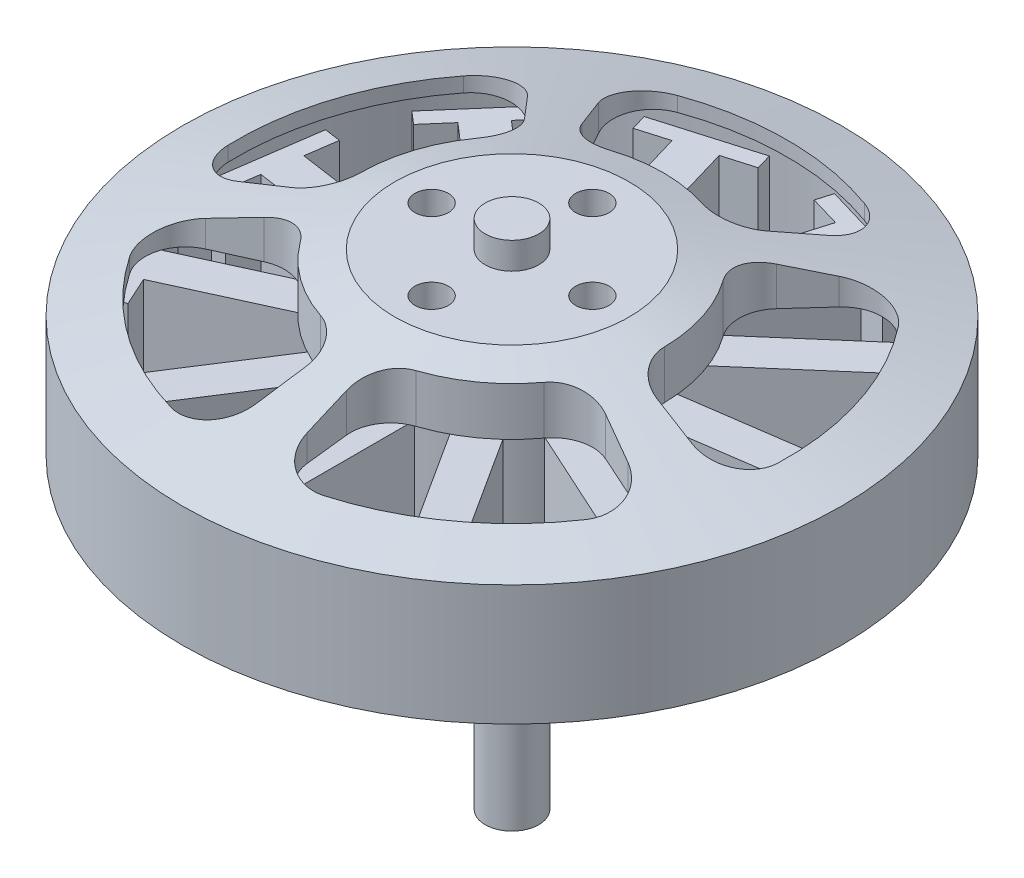
SolidWorks part; units mm, degrees
material "Acero aleado"
ref_plane "Alzado" through (0, 0, 0) normal (0, 0, 1) x (1, 0, 0)
ref_plane "Planta" through (0, 0, 0) normal (0, 1, 0) x (1, 0, 0)
ref_plane "Vista lateral" through (0, 0, 0) normal (1, 0, 0) x (0, 0, -1)
sketch "Croquis1" plane through (0, 0, 0) normal (0, 1, 0) x (1, 0, 0)
  circle A0 centre (0, 0) radius 24.6
  dimension "D1" = 49.2
extrude "Saliente-Extruir1" add sketch "Croquis1" along normal blind 9
sketch "Croquis2" plane through (0, 0, 0) normal (0, 0, 1) x (1, 0, 0)
  line L0 (-24.6, 9) -> (-8.75, 13.3)
  line L1 (-8.75, 13.3) -> (0, 13.3)
  line L2 (0, 13.3) -> (0, 9)
  line L3 (24.6, 9) -> (-24.6, 9) construction
  line L4 (0, 9) -> (-24.6, 9)
  dimension "D1" = 8.75
  dimension "D2" = 4.3
revolve "Revolución1" add sketch "Croquis2" angle 360 about L2
sketch "Croquis4" plane through (0, 0, 0) normal (0, -1, 0) x (1, 0, 0)
  circle A0 centre (0, 0) radius 22.8389
extrude "Cortar-Extruir1" cut sketch "Croquis4" against normal blind 9
sketch "Croquis5" plane through (0, 13.3, 0) normal (0, 1, 0) x (1, 0, 0)
  line L0 (-8.5704, 15.019) -> (-6.9301, 12.1446)
  line L1 (6.9301, 12.1446) -> (8.5704, 15.019)
  line L2 (0, 0) -> (0, 27.6667) construction
  line L3 (11.6356, 12.7921) -> (9.4086, 10.3438)
  line L4 (13.6917, -2.8381) -> (16.9324, -3.5098)
  line L5 (15.7616, -7.1131) -> (12.745, -5.7517)
  line L6 (1.5318, -13.8986) -> (1.8944, -17.1882)
  line L7 (-1.8944, -17.1882) -> (-1.5318, -13.8986)
  line L8 (-12.745, -5.7517) -> (-15.7616, -7.1131)
  line L9 (-16.9324, -3.5098) -> (-13.6917, -2.8381)
  line L10 (-9.4086, 10.3438) -> (-11.6356, 12.7921)
  arc A0 (3.4173, 10.7719) -> (-3.4173, 10.7719) centre (0, 0) ccw
  arc A1 (6.9844, 19.3273) -> (-6.9844, 19.3273) centre (0, 0) ccw
  arc A2 (6.9301, 12.1446) -> (3.4173, 10.7719) centre (4.3245, 13.6314) cw
  arc A3 (-6.9301, 12.1446) -> (-3.4173, 10.7719) centre (-4.3245, 13.6314) ccw
  arc A4 (8.5704, 15.019) -> (6.9844, 19.3273) centre (5.9648, 16.5059) ccw
  arc A5 (-8.5704, 15.019) -> (-6.9844, 19.3273) centre (-5.9648, 16.5059) cw
  arc A6 (11.3007, 0.0786) -> (9.1887, 6.5788) centre (0, 0) ccw
  arc A7 (20.5397, -0.6701) -> (16.2231, 12.615) centre (0, 0) ccw
  arc A8 (13.6917, -2.8381) -> (11.3007, 0.0786) centre (14.3006, 0.0995) cw
  arc A9 (9.4086, 10.3438) -> (9.1887, 6.5788) centre (11.6279, 8.3252) ccw
  arc A10 (16.9324, -3.5098) -> (20.5397, -0.6701) centre (17.5413, -0.5723) ccw
  arc A11 (11.6356, 12.7921) -> (16.2231, 12.615) centre (13.8548, 10.7735) cw
  arc A12 (3.5669, -10.7233) -> (9.0962, -6.706) centre (0, 0) ccw
  arc A13 (5.7098, -19.7415) -> (17.0108, -11.5308) centre (0, 0) ccw
  arc A14 (1.5318, -13.8986) -> (3.5669, -10.7233) centre (4.5137, -13.57) cw
  arc A15 (12.745, -5.7517) -> (9.0962, -6.706) centre (11.511, -8.4862) ccw
  arc A16 (1.8944, -17.1882) -> (5.7098, -19.7415) centre (4.8763, -16.8596) ccw
  arc A17 (15.7616, -7.1131) -> (17.0108, -11.5308) centre (14.5276, -9.8475) cw
  arc A18 (-9.0962, -6.706) -> (-3.5669, -10.7233) centre (0, 0) ccw
  arc A19 (-17.0108, -11.5308) -> (-5.7098, -19.7415) centre (0, 0) ccw
  arc A20 (-12.745, -5.7517) -> (-9.0962, -6.706) centre (-11.511, -8.4862) cw
  arc A21 (-1.5318, -13.8986) -> (-3.5669, -10.7233) centre (-4.5137, -13.57) ccw
  arc A22 (-15.7616, -7.1131) -> (-17.0108, -11.5308) centre (-14.5276, -9.8475) ccw
  arc A23 (-1.8944, -17.1882) -> (-5.7098, -19.7415) centre (-4.8763, -16.8596) cw
  arc A24 (-9.1887, 6.5788) -> (-11.3007, 0.0786) centre (0, 0) ccw
  arc A25 (-16.2231, 12.615) -> (-20.5397, -0.6701) centre (0, 0) ccw
  arc A26 (-9.4086, 10.3438) -> (-9.1887, 6.5788) centre (-11.6279, 8.3252) cw
  arc A27 (-13.6917, -2.8381) -> (-11.3007, 0.0786) centre (-14.3006, 0.0995) ccw
  arc A28 (-11.6356, 12.7921) -> (-16.2231, 12.615) centre (-13.8548, 10.7735) ccw
  arc A29 (-16.9324, -3.5098) -> (-20.5397, -0.6701) centre (-17.5413, -0.5723) cw
  point P65 (0, 0)
  dimension "D1" = 3
  dimension "D2" = 5
extrude "Cortar-Extruir2" cut sketch "Croquis5" against normal through all
sketch "Croquis3" plane through (0, 13.3, 0) normal (0, 1, 0) x (1, 0, 0)
  circle A0 centre (0, 0) radius 2
  dimension "D1" = 4
extrude "Saliente-Extruir2" add sketch "Croquis3" along normal blind 8 from offset 6 offset against normal yes
sketch "Croquis6" plane through (0, 7.3, 0) normal (0, -1, 0) x (1, 0, 0)
  line L0 (-1.4178, 20.2309) -> (-1.4178, 8.6919)
  line L1 (1.4178, 20.2309) -> (1.4178, 8.6919)
  line L2 (0, 0) -> (0, 19.3794) construction
  line L3 (-1.4178, 20.2309) -> (-3.7639, 20.2309)
  line L4 (-3.7639, 20.2309) -> (-3.7639, 21.4518)
  line L5 (-3.7639, 21.4518) -> (3.7639, 21.4518)
  line L6 (3.7639, 21.4518) -> (3.7639, 20.2309)
  line L7 (3.7639, 20.2309) -> (1.4178, 20.2309)
  line L8 (9.745, 17.7858) -> (3.5065, 8.0786)
  line L9 (12.1304, 16.2528) -> (5.8919, 6.5456)
  line L10 (9.745, 17.7858) -> (7.7713, 19.0542)
  line L11 (7.7713, 19.0542) -> (8.4313, 20.0813)
  line L12 (8.4313, 20.0813) -> (14.7641, 16.0115)
  line L13 (14.7641, 16.0115) -> (14.1041, 14.9844)
  line L14 (14.1041, 14.9844) -> (12.1304, 16.2528)
  line L15 (17.8137, 9.6939) -> (7.3175, 4.9004)
  line L16 (18.9916, 7.1146) -> (8.4954, 2.3211)
  line L17 (17.8137, 9.6939) -> (16.8391, 11.828)
  line L18 (16.8391, 11.828) -> (17.9496, 12.3352)
  line L19 (17.9496, 12.3352) -> (21.0768, 5.4876)
  line L20 (21.0768, 5.4876) -> (19.9663, 4.9805)
  line L21 (19.9663, 4.9805) -> (18.9916, 7.1146)
  line L22 (20.2268, -1.4758) -> (8.8052, 0.1663)
  line L23 (19.8232, -4.2825) -> (8.4017, -2.6403)
  line L24 (20.2268, -1.4758) -> (20.5606, 0.8464)
  line L25 (20.5606, 0.8464) -> (21.7691, 0.6727)
  line L26 (21.7691, 0.6727) -> (20.6978, -6.7785)
  line L27 (20.6978, -6.7785) -> (19.4893, -6.6047)
  line L28 (19.4893, -6.6047) -> (19.8232, -4.2825)
  line L29 (16.2179, -12.177) -> (7.4974, -4.6205)
  line L30 (14.3611, -14.3199) -> (5.6405, -6.7635)
  line L31 (16.2179, -12.177) -> (17.7543, -10.4039)
  line L32 (17.7543, -10.4039) -> (18.677, -11.2034)
  line L33 (18.677, -11.2034) -> (13.7473, -16.8925)
  line L34 (13.7473, -16.8925) -> (12.8247, -16.093)
  line L35 (12.8247, -16.093) -> (14.3611, -14.3199)
  line L36 (7.06, -19.012) -> (3.8091, -7.9404)
  line L37 (4.3394, -19.8108) -> (1.0885, -8.7393)
  line L38 (7.06, -19.012) -> (9.3111, -18.351)
  line L39 (9.3111, -18.351) -> (9.6551, -19.5224)
  line L40 (9.6551, -19.5224) -> (2.4322, -21.6432)
  line L41 (2.4322, -21.6432) -> (2.0883, -20.4718)
  line L42 (2.0883, -20.4718) -> (4.3394, -19.8108)
  line L43 (-4.3394, -19.8108) -> (-1.0885, -8.7393)
  line L44 (-7.06, -19.012) -> (-3.8091, -7.9404)
  line L45 (-4.3394, -19.8108) -> (-2.0883, -20.4718)
  line L46 (-2.0883, -20.4718) -> (-2.4322, -21.6432)
  line L47 (-2.4322, -21.6432) -> (-9.6551, -19.5224)
  line L48 (-9.6551, -19.5224) -> (-9.3111, -18.351)
  line L49 (-9.3111, -18.351) -> (-7.06, -19.012)
  line L50 (-14.3611, -14.3199) -> (-5.6405, -6.7635)
  line L51 (-16.2179, -12.177) -> (-7.4974, -4.6205)
  line L52 (-14.3611, -14.3199) -> (-12.8247, -16.093)
  line L53 (-12.8247, -16.093) -> (-13.7473, -16.8925)
  line L54 (-13.7473, -16.8925) -> (-18.677, -11.2034)
  line L55 (-18.677, -11.2034) -> (-17.7543, -10.4039)
  line L56 (-17.7543, -10.4039) -> (-16.2179, -12.177)
  line L57 (-19.8232, -4.2825) -> (-8.4017, -2.6403)
  line L58 (-20.2268, -1.4758) -> (-8.8052, 0.1663)
  line L59 (-19.8232, -4.2825) -> (-19.4893, -6.6047)
  line L60 (-19.4893, -6.6047) -> (-20.6978, -6.7785)
  line L61 (-20.6978, -6.7785) -> (-21.7691, 0.6727)
  line L62 (-21.7691, 0.6727) -> (-20.5606, 0.8464)
  line L63 (-20.5606, 0.8464) -> (-20.2268, -1.4758)
  line L64 (-18.9916, 7.1146) -> (-8.4954, 2.3211)
  line L65 (-17.8137, 9.6939) -> (-7.3175, 4.9004)
  line L66 (-18.9916, 7.1146) -> (-19.9663, 4.9805)
  line L67 (-19.9663, 4.9805) -> (-21.0768, 5.4876)
  line L68 (-21.0768, 5.4876) -> (-17.9496, 12.3352)
  line L69 (-17.9496, 12.3352) -> (-16.8391, 11.828)
  line L70 (-16.8391, 11.828) -> (-17.8137, 9.6939)
  line L71 (-12.1304, 16.2528) -> (-5.8919, 6.5456)
  line L72 (-9.745, 17.7858) -> (-3.5065, 8.0786)
  line L73 (-12.1304, 16.2528) -> (-14.1041, 14.9844)
  line L74 (-14.1041, 14.9844) -> (-14.7641, 16.0115)
  line L75 (-14.7641, 16.0115) -> (-8.4313, 20.0813)
  line L76 (-8.4313, 20.0813) -> (-7.7713, 19.0542)
  line L77 (-7.7713, 19.0542) -> (-9.745, 17.7858)
  arc A0 (-5.8919, 6.5456) -> (-7.3175, 4.9004) centre (0, 0) ccw
  arc A1 (3.5065, 8.0786) -> (1.4178, 8.6919) centre (0, 0) ccw
  arc A2 (7.3175, 4.9004) -> (5.8919, 6.5456) centre (0, 0) ccw
  arc A3 (8.8052, 0.1663) -> (8.4954, 2.3211) centre (0, 0) ccw
  arc A4 (7.4974, -4.6205) -> (8.4017, -2.6403) centre (0, 0) ccw
  arc A5 (3.8091, -7.9404) -> (5.6405, -6.7635) centre (0, 0) ccw
  arc A6 (-1.0885, -8.7393) -> (1.0885, -8.7393) centre (0, 0) ccw
  arc A7 (-5.6405, -6.7635) -> (-3.8091, -7.9404) centre (0, 0) ccw
  arc A8 (-8.4017, -2.6403) -> (-7.4974, -4.6205) centre (0, 0) ccw
  arc A10 (-8.4954, 2.3211) -> (-8.8052, 0.1663) centre (0, 0) ccw
  arc A11 (-1.4178, 8.6919) -> (-3.5065, 8.0786) centre (0, 0) ccw
  point P93 (0, 0)
  dimension "D1" = 11
extrude "Saliente-Extruir3" add sketch "Croquis6" along normal blind 8
sketch "Croquis7" plane through (0, -0.7, 0) normal (0, -1, 0) x (1, 0, 0)
  circle A0 centre (0, 0) radius 7.5
  dimension "D1" = 15
extrude "Saliente-Extruir4" add sketch "Croquis7" along normal blind 5
sketch "Croquis8" plane through (0, -5.7, 0) normal (0, -1, 0) x (1, 0, 0)
  circle A0 centre (0, 0) radius 12.25
  dimension "D1" = 24.5
extrude "Saliente-Extruir5" add sketch "Croquis8" along normal blind 1.2
sketch "Croquis9" plane through (0, -6.9, 0) normal (0, -1, 0) x (1, 0, 0)
  circle A0 centre (0, 0) radius 2
  dimension "D1" = 4
extrude "Saliente-Extruir6" add sketch "Croquis9" along normal blind 16
sketch "Croquis10" plane through (0, -6.9, 0) normal (0, -1, 0) x (1, 0, 0)
  line L0 (-1.85, 4.2703) -> (-1.85, 1.6815)
  line L1 (1.85, 4.2703) -> (1.85, 1.6815)
  line L2 (-1.85, 4.2703) -> (1.85, 4.2703)
  line L3 (0, 0) -> (0, 5.3901) construction
  arc A0 (-1.85, 1.6815) -> (1.85, 1.6815) centre (0, 0) ccw
  point P7 (0, 4.2703)
  dimension "D1" = 3.7
  dimension "D2" = 5
extrude "Saliente-Extruir7" add sketch "Croquis10" along normal blind 0.8
sketch "Croquis11" plane through (0, 13.3, 0) normal (0, 1, 0) x (1, 0, 0)
  circle A0 centre (0, 0) radius 6 construction
  circle A1 centre (0, -6) radius 1.25
  circle A2 centre (6, 0) radius 1.25
  circle A3 centre (0, 6) radius 1.25
  circle A4 centre (-6, 0) radius 1.25
  dimension "D1" = 12
  dimension "D2" = 2.5
extrude "Cortar-Extruir3" cut sketch "Croquis11" against normal blind 3
sketch "Croquis12" plane through (0, -6.9, 0) normal (0, -1, 0) x (1, 0, 0)
  line L0 (0, -8) -> (0, 8) construction
  line L1 (-9.5, 0) -> (9.5, 0) construction
  circle A0 centre (0, 8) radius 1.3484
  circle A1 centre (0, -8) radius 1.3484
  circle A2 centre (-9.5, 0) radius 1.3484
  circle A3 centre (9.5, 0) radius 1.3484
  point P4 (0, 0)
  point P10 (0, 0)
  dimension "D1" = 16
  dimension "D2" = 19
extrude "Cortar-Extruir4" cut sketch "Croquis12" against normal blind 6
sketch "Croquis13" plane through (0, -5.7, 0) normal (0, 1, 0) x (1, 0, 0)
  line L0 (-6.9089, 2.7478) -> (-3.1846, 6.4721)
  line L1 (-3.1846, 6.4721) -> (-16.0348, 19.3223)
  line L2 (-16.0348, 19.3223) -> (-19.7591, 15.598)
  line L3 (-19.7591, 15.598) -> (-6.9089, 2.7478)
extrude "Saliente-Extruir8" add sketch "Croquis13" along normal blind 2 from offset 1
